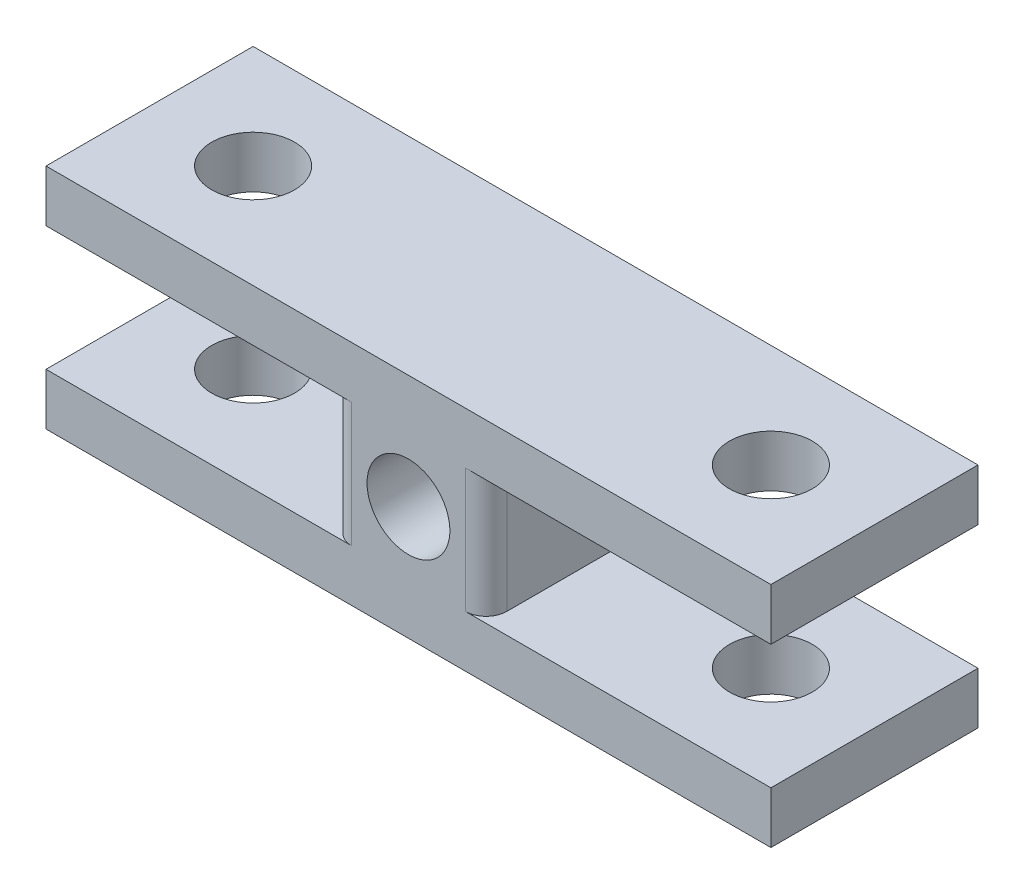
SolidWorks part; units mm, degrees
ref_plane "Front Plane" through (0, 0, 0) normal (0, 0, 1) x (1, 0, 0)
ref_plane "Top Plane" through (0, 0, 0) normal (0, 1, 0) x (1, 0, 0)
ref_plane "Right Plane" through (0, 0, 0) normal (1, 0, 0) x (0, 0, -1)
sketch "Sketch1" plane through (0, 0, 0) normal (0, 1, 0) x (1, 0, 0)
  line L0 (0, -55) -> (0, 55) construction
  line L5 (-35, 10) -> (35, 10)
  line L6 (-35, 10) -> (-35, -10)
  line L7 (-35, -10) -> (35, -10)
  line L8 (35, 10) -> (35, -10)
  line L9 (-35, 10) -> (35, -10) construction
  line L10 (-35, -10) -> (35, 10) construction
  circle A0 centre (-25, 0) radius 4
  circle A1 centre (25, 0) radius 4
  point P0 (0, 0)
  dimension "D3" = 8
  dimension "D1" = 20
  dimension "D2" = 70
  dimension "D4" = 25
extrude "Boss-Extrude1" add sketch "Sketch1" along normal blind 5
sketch "Sketch2" plane through (0, 5, 0) normal (0, 1, 0) x (1, 0, 0)
  line L0 (35, 10) -> (-35, 10) construction
  line L1 (-7.5, -10) -> (7.5, -10)
  line L2 (-7.5, -10) -> (-7.5, 10)
  line L3 (-7.5, 10) -> (7.5, 10)
  line L4 (7.5, -10) -> (7.5, 10)
  line L5 (-7.5, -10) -> (7.5, 10) construction
  line L6 (-7.5, 10) -> (7.5, -10) construction
  point P0 (0, 0)
  dimension "D1" = 15
extrude "Boss-Extrude2" add sketch "Sketch2" along normal blind 6
ref_plane "Plane1" through (0, 11, 0) normal (0, 1, 0) x (1, 0, 0)
mirror "Mirror3" about plane through (0, 11, 0) normal (0, 1, 0) of "Boss-Extrude2", "Boss-Extrude1"
mirror "Mirror4" about plane through (0, 11, 0) normal (0, 1, 0) of "Boss-Extrude1"
sketch "Sketch3" plane through (0, 0, -10) normal (0, 0, -1) x (-1, 0, 0)
  line L0 (-7.5, 17) -> (-7.5, 5) construction
  line L1 (-35, 0) -> (35, 0) construction
  circle A0 centre (0, 11) radius 4
  dimension "D1" = 8
  dimension "D2" = 7.5
  dimension "D3" = 11
extrude "Cut-Extrude1" cut sketch "Sketch3" against normal through all
fillet "Fillet1" radius 2 4 edges at (-7.5, 11, 10) (7.5, 11, 10) (-7.5, 11, -10) (7.5, 11, -10)
